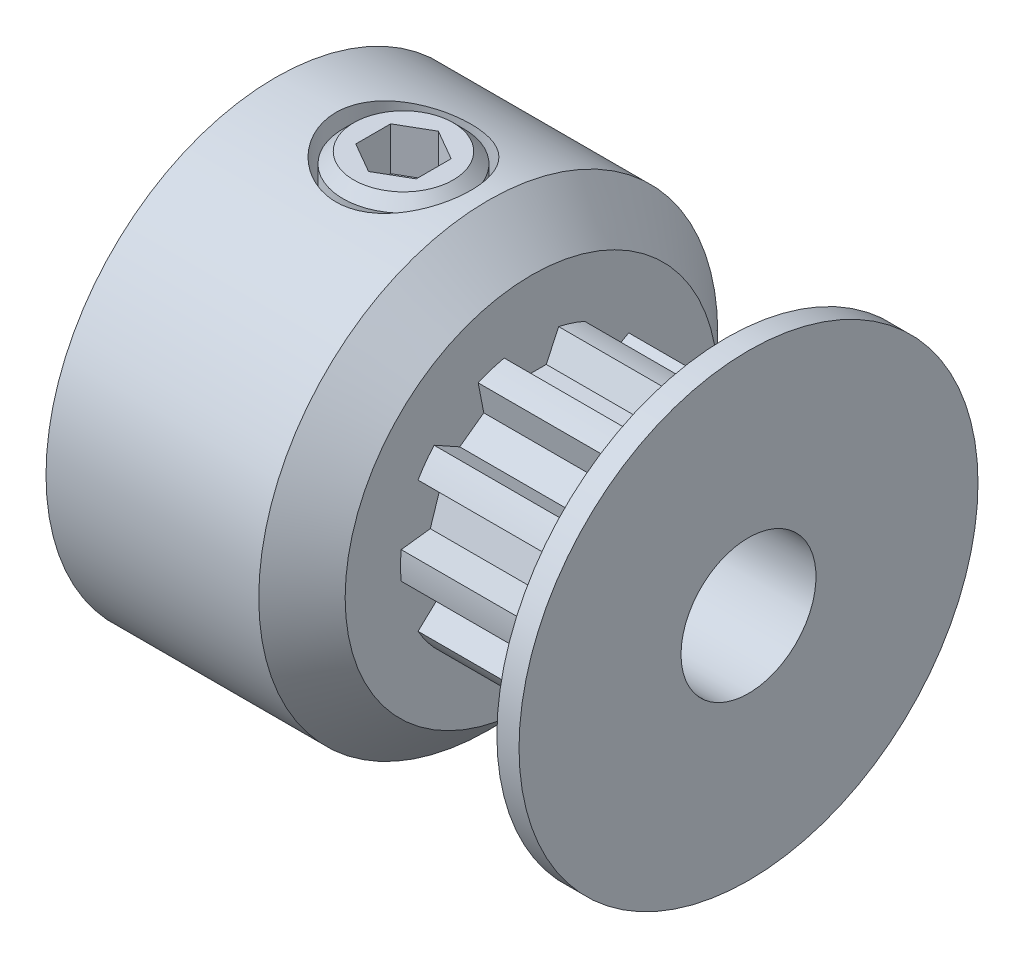
SolidWorks part; units mm, degrees
ref_plane "Front Plane" through (0, 0, 0) normal (0, 0, 1) x (1, 0, 0)
ref_plane "Top Plane" through (0, 0, 0) normal (0, 1, 0) x (1, 0, 0)
ref_plane "Right Plane" through (0, 0, 0) normal (1, 0, 0) x (0, 0, -1)
sketch "Sketch2" plane through (0, 0, 0) normal (1, 0, 0) x (0, 0, -1)
  line L3 (0, 0) -> (0, 2.413) construction
  line L6 (0, -2.921) -> (0, -3.2385) construction
  line L7 (-0.5715, 2.8645) -> (-0.3491, 2.3876)
  line L8 (0.5715, 2.8645) -> (0.3491, 2.3876)
  line L9 (-0.5715, 2.8645) -> (-0.6405, 3.0124)
  line L10 (0.5715, 2.8645) -> (0.6405, 3.0124)
  line L12 (-0.3491, 2.3876) -> (0.3491, 2.3876)
  line L14 (0, 2.921) -> (0, 3.2385) construction
  line L15 (0, 0) -> (0, -1.143) construction
  circle A0 centre (0, 0) radius 3.2385 construction
  circle A1 centre (0, 0) radius 2.413 construction
  circle A2 centre (0, 0) radius 2.921 construction
  arc A7 (0.6405, 3.0124) -> (-0.6405, 3.0124) centre (0, 0) ccw
  point P5 (0, 3.0798)
  dimension "D3" = 0.3175
  dimension "D1" = 50
sketch "Sketch1" plane through (0, 0, 0) normal (0, 0, 1) x (1, 0, 0)
  line L0 (-5.5626, 0) -> (5.5626, 0) construction
  line L1 (-5.5626, 1.5875) -> (5.5626, 1.5875)
  line L2 (-5.5626, 1.5875) -> (-5.5626, 5.3975)
  line L3 (-5.5626, 5.3975) -> (-0.5588, 5.3975)
  line L4 (-0.5588, 5.3975) -> (0.4572, 4.3815)
  line L5 (0.4572, 4.3815) -> (0.4572, 3.2385)
  line L6 (0.4572, 3.2385) -> (4.5212, 3.2385)
  line L7 (4.5212, 3.2385) -> (4.5212, 3.81)
  line L8 (4.5212, 3.2385) -> (5.5626, 3.2385) construction
  line L9 (5.0419, 5.3975) -> (5.5626, 5.3975)
  line L10 (5.5626, 5.3975) -> (5.5626, 1.5875)
  line L11 (5.0419, 3.2385) -> (5.0419, 5.3975) construction
  line L12 (-3.0607, 5.3975) -> (-3.0607, 1.5875) construction
  arc A0 (4.5212, 3.81) -> (5.0419, 5.3975) centre (7.2015, 3.81) cw
  dimension "Bore Size" = 3.175
  dimension "Overall Width" = 11.1252
  dimension "Inside Width" = 4.064
  dimension "Outside Width" = 5.1054
  dimension "Hub Dia" = 10.795
  dimension "OD" = 10.795
  dimension "D1" = 45
  dimension "D2" = 6.477
  dimension "D3" = 1.143
  dimension "D4" = 0.5715
revolve "Revolve1" add sketch "Sketch1" angle 360 mid plane about L0
sketch "Sketch4" plane through (0.4572, 0, 0) normal (1, 0, 0) x (0, 0, -1)
  circle A0 centre (0, 0) radius 3.0798
  circle A1 centre (0, 0) radius 3.2385 construction
  circle A2 centre (0, 0) radius 3.2385
extrude "Cut-Extrude2" cut sketch "Sketch4" along normal up to surface (4.064 mm away) up to face at (4.5212, 0, 3.2385)
sketch "Sketch3" plane through (0.4572, 0, 0) normal (1, 0, 0) x (0, 0, -1)
  line L2 (-0.5715, 2.8645) -> (-0.3491, 2.3876) construction
  line L3 (-0.3491, 2.3876) -> (0.3491, 2.3876) construction
  line L4 (0.5715, 2.8645) -> (0.3491, 2.3876) construction
  line L5 (-0.6405, 3.0124) -> (-0.3491, 2.3876)
  line L6 (-0.3491, 2.3876) -> (0.3491, 2.3876)
  line L7 (0.6405, 3.0124) -> (0.3491, 2.3876)
  arc A1 (0.6405, 3.0124) -> (-0.6405, 3.0124) centre (0, 0) ccw construction
  arc A2 (0.6405, 3.0124) -> (-0.6405, 3.0124) centre (0, 0) ccw
extrude "Cut-Extrude1" cut sketch "Sketch3" along normal up to surface (4.064 mm away) up to face at (4.5212, 0, 3.81)
pattern_circular "CirPattern1" count 10 over 360 about axis through (0, 0, 0) along (1, 0, 0) of "Cut-Extrude1"
sketch "Sketch5" plane through (0, 0, 0) normal (0, 0, 1) x (1, 0, 0)
  line L1 (4.5212, 3.81) -> (4.5212, -3.81) construction
  point P0 (4.5212, 0)
sketch "Sketch6" plane through (0, 0, 0) normal (0, 1, 0) x (1, 0, 0)
  line L0 (-5.5626, 0) -> (-4.1402, 0) construction
  line L1 (-5.5626, 5.3975) -> (-5.5626, -5.3975) construction
  line L2 (0.4572, 0) -> (-0.9652, 0) construction
  line L3 (0.4572, -0.3491) -> (0.4572, 0.3491) construction
  circle A0 centre (-2.5527, 0) radius 1.5875
  dimension "D1" = 3.175
extrude "Cut-Extrude3" cut sketch "Sketch6" along normal through all
sketch "Sketch7" plane through (0, 0, 0) normal (0, 0, 1) x (1, 0, 0)
  line L0 (-3.7211, 5.3975) -> (-2.5527, 5.3975)
  line L1 (-3.9751, 5.1435) -> (-3.9751, 2.2225)
  line L2 (-3.9751, 2.2225) -> (-3.7211, 1.9685)
  line L3 (-3.7211, 1.9685) -> (-2.5527, 1.9685)
  line L4 (-2.5527, 1.9685) -> (-2.5527, 5.3975) construction
  line L6 (-3.9751, 5.1435) -> (-3.7211, 5.3975)
  line L7 (-5.5626, 5.3975) -> (-0.5588, 5.3975) construction
  line L8 (-2.5527, 5.3975) -> (-2.5527, 1.9685)
  point P0 (-3.9751, 5.3975)
  point P4 (-3.9751, 1.9685)
  dimension "D1" = 2.8448
  dimension "D2" = 0.381
revolve "Revolve2" add sketch "Sketch7" angle 360 mid plane about L4
sketch "Sketch8" plane through (0, 5.3975, 0) normal (0, 1, 0) x (1, 0, 0)
  line L1 (-2.5527, 0.8212) -> (-3.2639, 0.4106)
  line L2 (-3.2639, 0.4106) -> (-3.2639, -0.4106)
  line L3 (-3.2639, -0.4106) -> (-2.5527, -0.8212)
  line L4 (-2.5527, -0.8212) -> (-1.8415, -0.4106)
  line L5 (-1.8415, -0.4106) -> (-1.8415, 0.4106)
  line L6 (-1.8415, 0.4106) -> (-2.5527, 0.8212)
  circle A0 centre (-2.5527, 0) radius 0.7112 construction
  dimension "D1" = 1.4224
extrude "Cut-Extrude4" cut sketch "Sketch8" against normal blind 1.016
pattern_circular "CirPattern2" [suppressed] count 2 over 90
pattern_circular "CirPattern3" [suppressed] count 2 over 90
equation "\"D3@Sketch2\" = (\"hs@Sketch2\"-\"ht@Sketch2\")/2"
equation "\"D2@Sketch1\" = \"PD@Sketch2\""
equation "\"D3@Sketch1\" = \"hs@Sketch2\""
equation "\"D4@Sketch1\" = \"D3@Sketch1\"/2"
